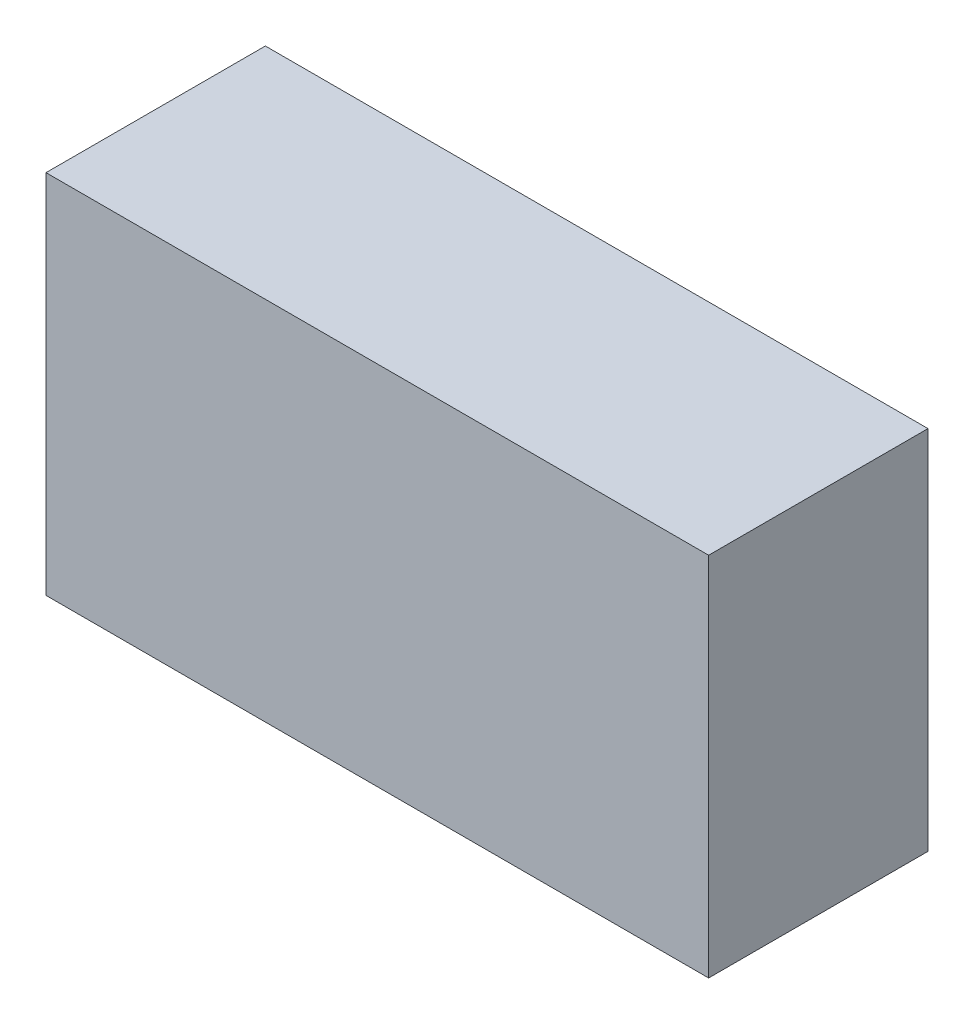
SolidWorks part; units mm, degrees
ref_plane "Front Plane" through (0, 0, 0) normal (0, 0, 1) x (1, 0, 0)
ref_plane "Top Plane" through (0, 0, 0) normal (0, 1, 0) x (1, 0, 0)
ref_plane "Right Plane" through (0, 0, 0) normal (1, 0, 0) x (0, 0, -1)
sketch "Sketch1" plane through (0, 0, 0) normal (0, 0, 1) x (1, 0, 0)
  line L0 (-56.9355, 77.7714) -> (-79.2368, 77.7714) construction
  line L1 (-79.0368, 77.5714) -> (-57.1355, 77.5714)
  line L2 (-79.0368, 77.5714) -> (-79.0368, 65.47)
  line L3 (-79.0368, 65.47) -> (-57.1355, 65.47)
  line L4 (-57.1355, 77.5714) -> (-57.1355, 65.47)
  line L5 (-56.9355, 65.27) -> (-79.2368, 65.27) construction
  line L6 (-56.9355, 65.7086) -> (-56.9355, 77.7714) construction
  line L7 (-79.2368, 77.7714) -> (-79.2368, 65.27) construction
  dimension "D1" = 0.2
  dimension "D2" = 0.2
  dimension "D3" = 0.2
  dimension "D4" = 0.2
extrude "Boss-Extrude1" add sketch "Sketch1" along normal blind 7.25
shell "Shell1" thickness 0.5
equation "\"D1@Sketch1\"=0.2"
equation "\"D3@Sketch1\"=\"D1@Sketch1\""
equation "\"D2@Sketch1\"=\"D1@Sketch1\""
equation "\"D4@Sketch1\"=\"D1@Sketch1\""
